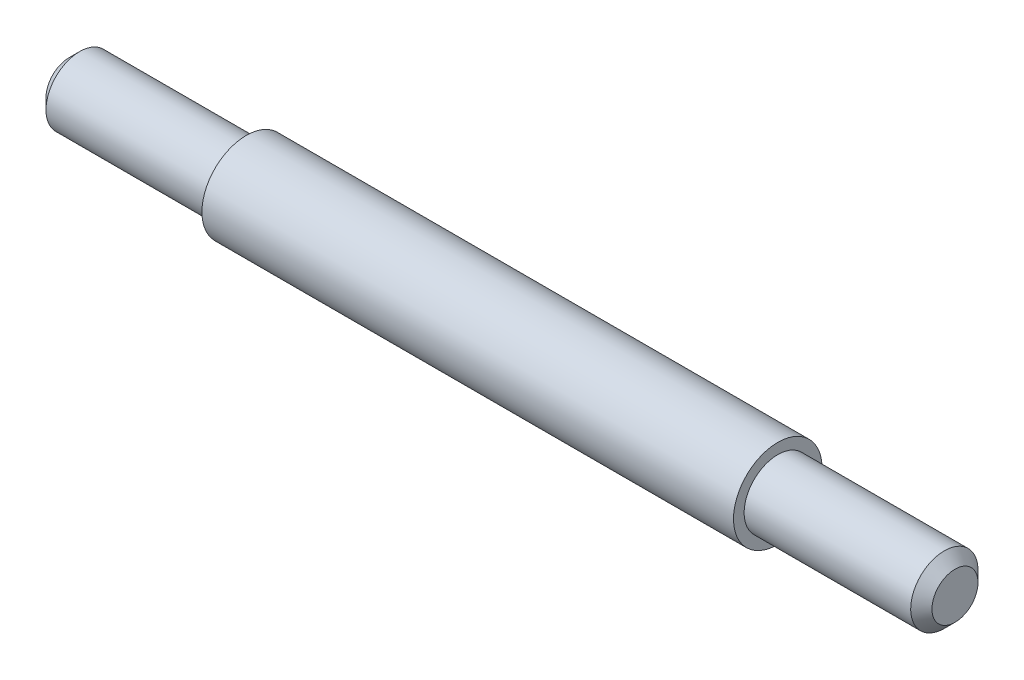
SolidWorks part; units mm, degrees
ref_plane "Front Plane" through (0, 0, 0) normal (0, 0, 1) x (1, 0, 0)
ref_plane "Top Plane" through (0, 0, 0) normal (0, 1, 0) x (1, 0, 0)
ref_plane "Right Plane" through (0, 0, 0) normal (1, 0, 0) x (0, 0, -1)
sketch "Sketch1" plane through (0, 0, 0) normal (0, 0, 1) x (1, 0, 0)
  line L0 (-0.75, 0.125) -> (0.75, 0.125)
  line L1 (0.75, 0.125) -> (0.75, 0.095)
  line L2 (0.75, 0.095) -> (1.25, 0.095)
  line L3 (1.25, 0.095) -> (1.25, 0)
  line L4 (1.25, 0) -> (-1.25, 0)
  line L5 (0, 0.4433) -> (0, -0.2593) construction
  line L6 (-1.25, 0.095) -> (-1.25, 0)
  line L7 (-0.75, 0.125) -> (-0.75, 0.095)
  line L8 (-0.75, 0.095) -> (-1.25, 0.095)
  point P11 (0, 0)
  point P13 (0, 0.125)
  dimension "D1" = 1.5
  dimension "D2" = 0.5
  dimension "D3" = 0.125
  dimension "D4" = 0.095
revolve "Revolve1" add sketch "Sketch1" angle 360 about L4
chamfer "Chamfer1" distance 0.03 1 edges at (-1.25, 0.095, 0)
chamfer "Chamfer2" distance 0.03 1 edges at (1.25, 0.095, 0)
